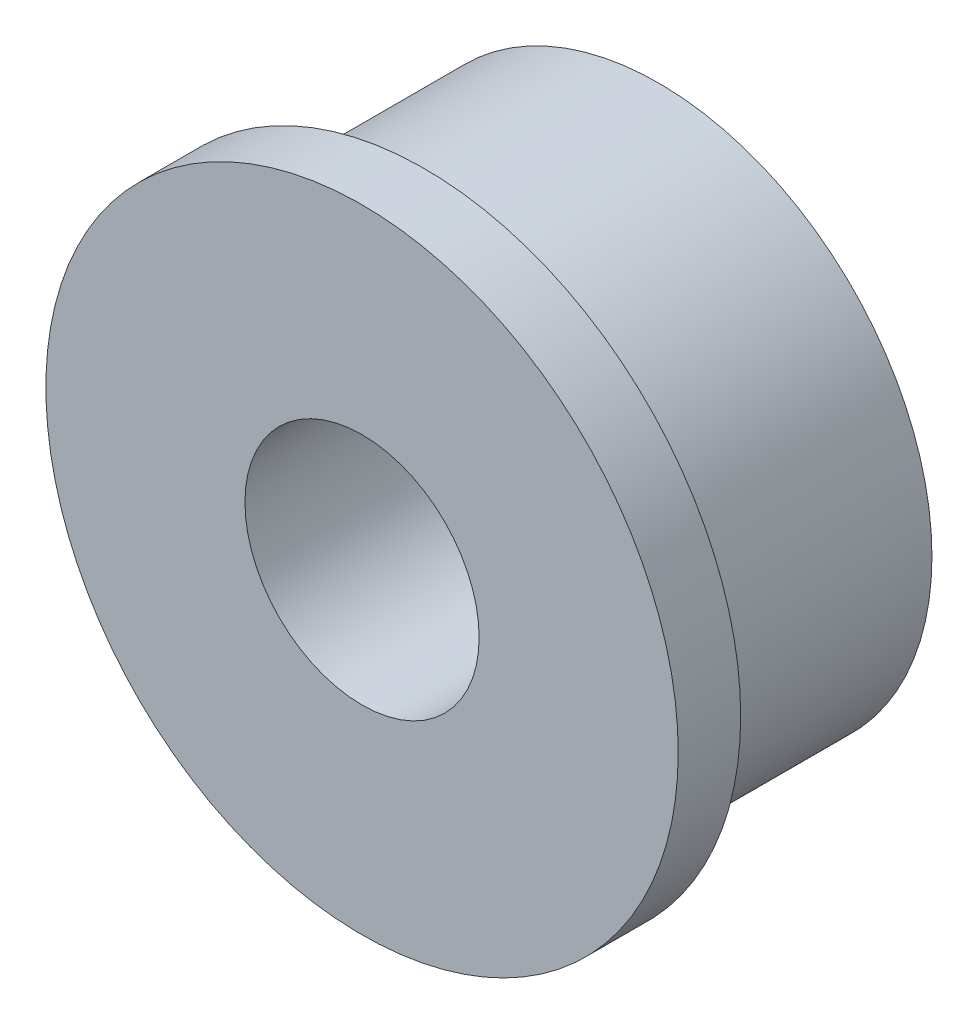
SolidWorks part; units mm, degrees
material "AISI 类型 A2 刀具钢"
ref_plane "前视基准面" through (0, 0, 0) normal (0, 0, 1) x (1, 0, 0)
ref_plane "上视基准面" through (0, 0, 0) normal (0, 1, 0) x (1, 0, 0)
ref_plane "右视基准面" through (0, 0, 0) normal (1, 0, 0) x (0, 0, -1)
sketch "草图1" plane through (0, 0, 0) normal (0, 0, 1) x (1, 0, 0)
  circle A0 centre (0, 0) radius 3.5
  circle A1 centre (0, 0) radius 1.5
  dimension "D1" = 7
  dimension "D2" = 3
extrude "凸台-拉伸1" add sketch "草图1" along normal blind 3
sketch "草图2" plane through (0, 0, 3) normal (0, 0, 1) x (1, 0, 0)
  circle A0 centre (0, 0) radius 1.5
  circle A1 centre (0, 0) radius 4.05
  dimension "D1" = 3
  dimension "D2" = 8.1
extrude "凸台-拉伸2" add sketch "草图2" along normal blind 0.8
